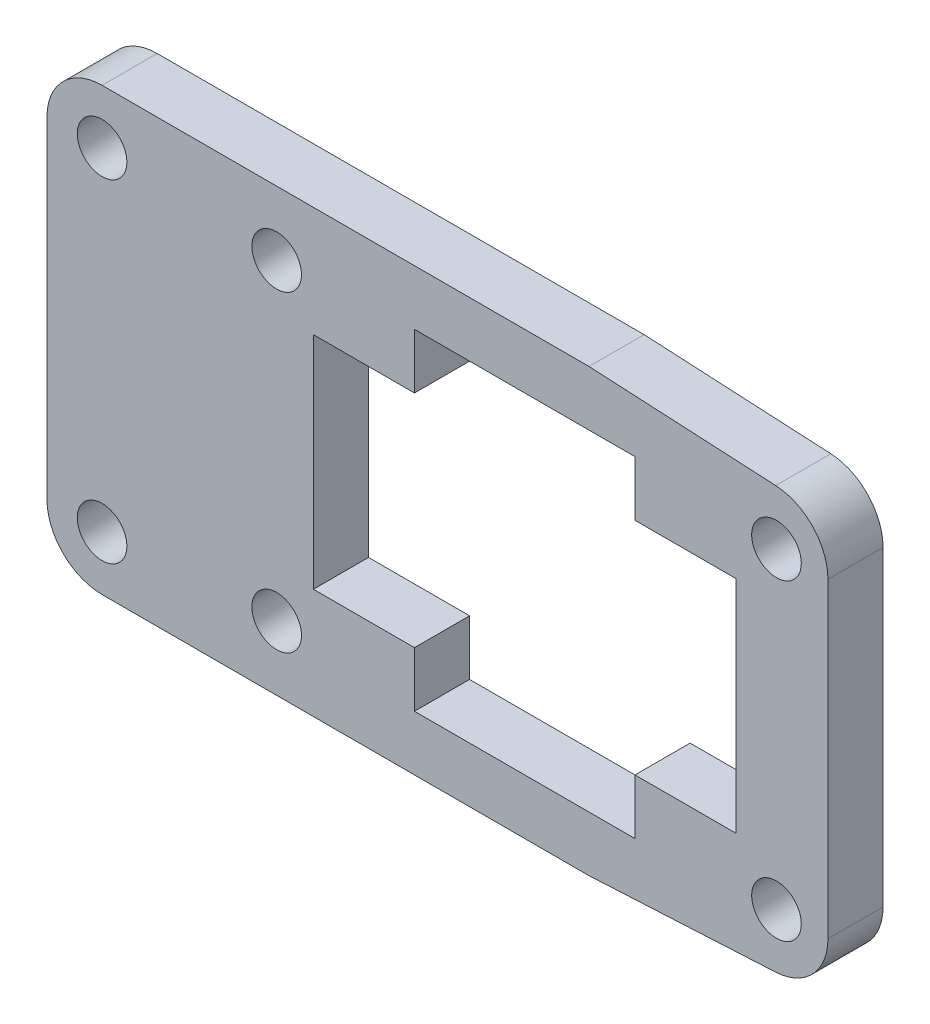
SolidWorks part; units mm, degrees
ref_plane "前视基准面" through (0, 0, 0) normal (0, 0, 1) x (1, 0, 0)
ref_plane "上视基准面" through (0, 0, 0) normal (0, 1, 0) x (1, 0, 0)
ref_plane "右视基准面" through (0, 0, 0) normal (1, 0, 0) x (0, 0, -1)
ref_plane "基准面4" through (0, 0, 0) normal (0, 0, -1) x (-1, 0, 0)
sketch "草图1" plane through (0, 0, 0) normal (0, 0, -1) x (-1, 0, 0)
  line L0 (15.6573, 3) -> (15.6573, 20.9998)
  line L1 (12.6573, 23.9998) -> (-13.8437, 23.9998)
  line L2 (-13.8437, 23.9998) -> (-24.0011, 23.4678)
  line L3 (-26.8442, 20.4719) -> (-26.8442, 3.5289)
  line L4 (-24.0014, 0.533) -> (-13.8437, 0)
  line L5 (-13.8437, 0) -> (12.6573, 0)
  line L6 (-4.3434, 20.9998) -> (-4.3434, 17.9998)
  line L7 (-4.3434, 17.9998) -> (1.1565, 17.9998)
  line L8 (1.1565, 17.9998) -> (1.1565, 6)
  line L9 (1.1565, 6) -> (-4.3434, 6)
  line L10 (-4.3434, 6) -> (-4.3434, 3)
  line L11 (-4.3434, 3) -> (-16.3434, 3)
  line L12 (-16.3434, 3) -> (-16.3434, 6)
  line L13 (-16.3434, 6) -> (-21.8432, 6)
  line L14 (-21.8432, 6) -> (-21.8432, 17.9998)
  line L15 (-21.8432, 17.9998) -> (-16.3434, 17.9998)
  line L16 (-16.3434, 17.9998) -> (-16.3434, 20.9998)
  line L17 (-16.3434, 20.9998) -> (-4.3434, 20.9998)
  arc A0 (12.6573, 0) -> (15.6573, 3) centre (12.6573, 3) ccw
  arc A1 (15.6573, 20.9998) -> (12.6573, 23.9998) centre (12.6573, 20.9998) ccw
  arc A2 (-24.0011, 23.4678) -> (-26.8442, 20.4719) centre (-23.8442, 20.4719) ccw
  arc A3 (-26.8442, 3.5289) -> (-24.0014, 0.533) centre (-23.8442, 3.5289) ccw
  circle A4 centre (-24.044, 3.5011) radius 1.35
  circle A5 centre (-24.044, 20.4984) radius 1.35
  circle A6 centre (3.156, 20.4984) radius 1.35
  circle A7 centre (3.156, 3.5011) radius 1.35
  circle A8 centre (12.6575, 2.95) radius 1.35
  circle A9 centre (12.6575, 21.049) radius 1.35
extrude "凸台-拉伸1" add sketch "草图1" against normal blind 3
